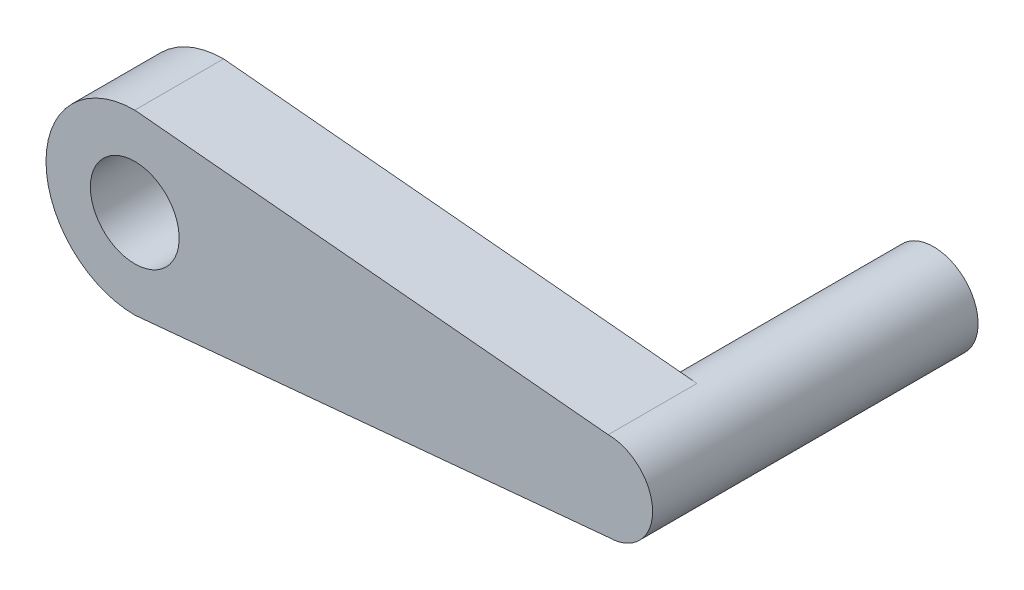
SolidWorks part; units mm, degrees
ref_plane "Front Plane" through (0, 0, 0) normal (0, 0, 1) x (1, 0, 0)
ref_plane "Top Plane" through (0, 0, 0) normal (0, 1, 0) x (1, 0, 0)
ref_plane "Right Plane" through (0, 0, 0) normal (1, 0, 0) x (0, 0, -1)
sketch "Sketch1" plane through (0, 0, 0) normal (0, 0, 1) x (1, 0, 0)
  line L2 (0, -9.525) -> (50.8, -4.7625)
  line L3 (50.8, 4.7625) -> (0, 9.525)
  arc A2 (1.7704, 9.359) -> (1.7704, -9.359) centre (0, 0) ccw
  arc A3 (50.8, -4.7625) -> (50.8, 4.7625) centre (50.8, 0) ccw
  circle A4 centre (0, 0) radius 4.7625
  point P10 (50.8, 0)
  dimension "D1" = 19.05
  dimension "D2" = 9.525
  dimension "D4" = 9.525
  dimension "D3" = 50.8
extrude "Boss-Extrude1" add sketch "Sketch1" along normal blind 9.525 contours L2 A3 L3 A2 A4
sketch "Sketch4" plane through (0, 0, 0) normal (0, 0, -1) x (-1, 0, 0)
  circle A0 centre (-50.8, 0) radius 4.7625
  dimension "D1" = 9.525
extrude "Boss-Extrude4" add sketch "Sketch4" along normal blind 25.4
